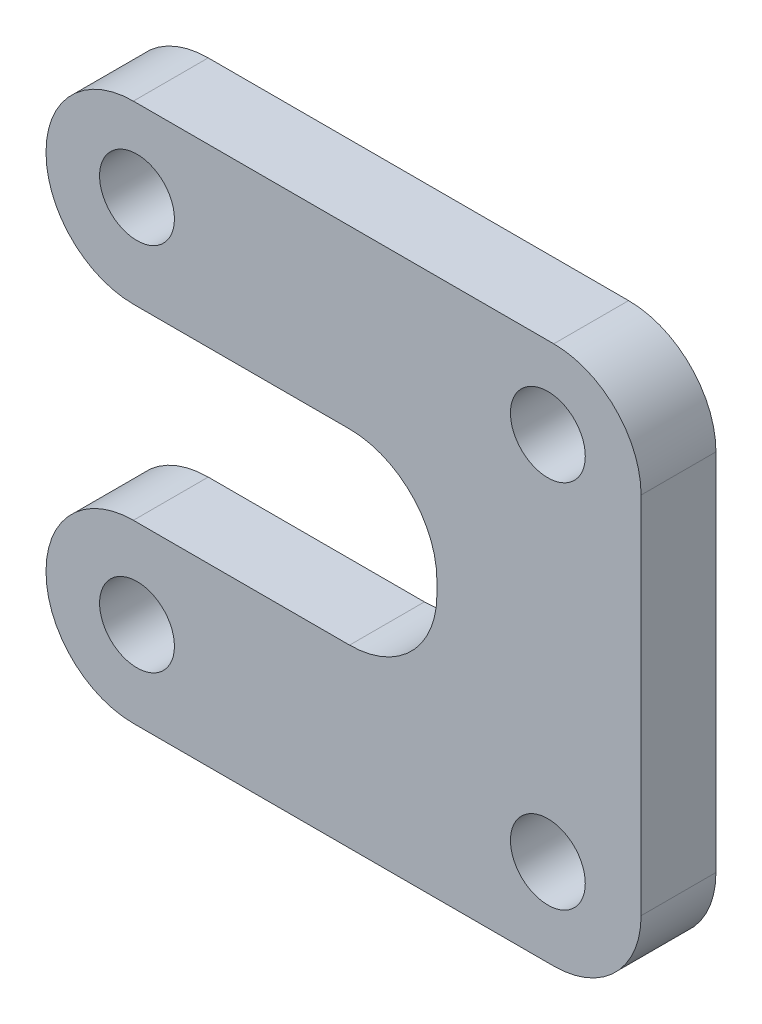
SolidWorks part; units mm, degrees
ref_plane "Front Plane" through (0, 0, 0) normal (0, 0, 1) x (1, 0, 0)
ref_plane "Top Plane" through (0, 0, 0) normal (0, 1, 0) x (1, 0, 0)
ref_plane "Right Plane" through (0, 0, 0) normal (1, 0, 0) x (0, 0, -1)
sketch "Sketch1" plane through (0, 0, 0) normal (0, 0, 1) x (1, 0, 0)
  line L40 (-96.6752, 41.5294) -> (-96.6752, 41.4294)
  line L41 (-89.6752, 48.5294) -> (-55.9788, 48.5294)
  line L43 (-48.9788, 41.5294) -> (-48.9788, 12.3294)
  line L44 (-55.9788, 5.3294) -> (-89.6752, 5.3294)
  line L46 (-89.6752, 34.4294) -> (-72.3465, 34.4294)
  line L47 (-89.6752, 19.4294) -> (-72.3465, 19.4294)
  line L48 (-65.3465, 27.4294) -> (-65.3465, 26.4294)
  line L49 (-96.6752, 12.4294) -> (-96.6752, 12.3294)
  arc A23 (-55.9788, 5.3294) -> (-48.9788, 12.3294) centre (-55.9788, 12.3294) ccw
  arc A24 (-55.9788, 48.5294) -> (-48.9788, 41.5294) centre (-55.9788, 41.5294) cw
  arc A25 (-96.6752, 12.3294) -> (-89.6752, 5.3294) centre (-89.6752, 12.3294) ccw
  arc A26 (-89.6752, 19.4294) -> (-96.6752, 12.4294) centre (-89.6752, 12.4294) ccw
  arc A27 (-96.6752, 41.4294) -> (-89.6752, 34.4294) centre (-89.6752, 41.4294) ccw
  arc A28 (-89.6752, 48.5294) -> (-96.6752, 41.5294) centre (-89.6752, 41.5294) ccw
  arc A29 (-65.3465, 26.4294) -> (-72.3465, 19.4294) centre (-72.3465, 26.4294) cw
  arc A30 (-72.3465, 34.4294) -> (-65.3465, 27.4294) centre (-72.3465, 27.4294) cw
extrude "Boss-Extrude1" add sketch "Sketch1" along normal blind 6
sketch "Sketch2" plane through (0, 0, 6) normal (0, 0, 1) x (1, 0, 0)
  circle A0 centre (-89.3854, 41.9908) radius 3
  circle A1 centre (-56.4519, 41.9908) radius 3
  circle A2 centre (-56.4519, 12.3294) radius 3
  circle A3 centre (-89.3854, 12.3294) radius 3
  point P4 (-56.4519, 41.9908)
  point P7 (-56.4519, 12.3294)
  point P10 (-89.3854, 12.7234)
  point P11 (0, 0)
  point P12 (-87.6135, 12.3294)
  point P13 (0, 0)
  point P14 (-89.3854, 12.3294)
extrude "Cut-Extrude1" cut sketch "Sketch2" against normal blind 10
